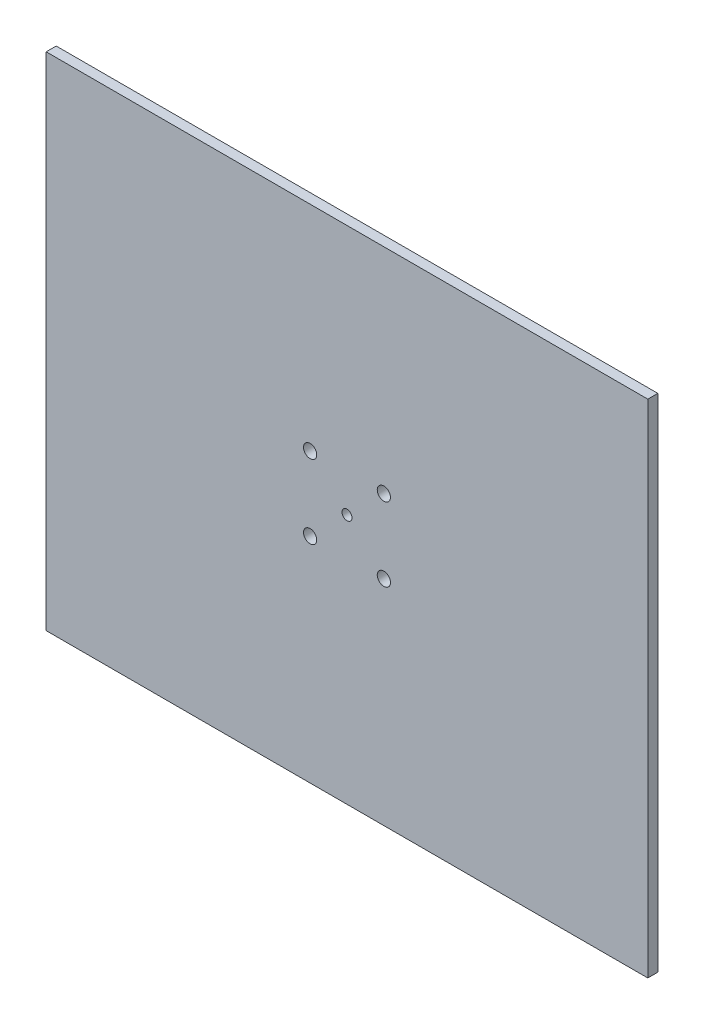
SolidWorks part; units mm, degrees
ref_plane "前视基准面" through (0, 0, 0) normal (0, 0, 1) x (1, 0, 0)
ref_plane "上视基准面" through (0, 0, 0) normal (0, 1, 0) x (1, 0, 0)
ref_plane "右视基准面" through (0, 0, 0) normal (1, 0, 0) x (0, 0, -1)
sketch "草图1" plane through (0, 0, 0) normal (0, 0, 1) x (1, 0, 0)
  line L0 (-18.3848, 18.3848) -> (0, 0) construction
  line L1 (150, -125) -> (-150, -125)
  line L2 (150, -125) -> (150, 125)
  line L3 (150, 125) -> (-150, 125)
  line L4 (-150, -125) -> (-150, 125)
  line L5 (150, -125) -> (-150, 125) construction
  line L6 (150, 125) -> (-150, -125) construction
  line L7 (0, 0) -> (0, 75.2853) construction
  line L8 (0, 0) -> (89.5261, 0) construction
  circle A0 centre (-18.3848, 18.3848) radius 3.3
  circle A1 centre (18.3848, 18.3848) radius 3.3
  circle A2 centre (18.3848, -18.3848) radius 3.3
  circle A3 centre (-18.3848, -18.3848) radius 3.3
  circle A4 centre (0, 0) radius 2.5
  point P0 (0, 0)
  dimension "D3" = 6.6
  dimension "D6" = 5
  dimension "D1" = 250
  dimension "D2" = 300
  dimension "D4" = 26
  dimension "D5" = 45
extrude "凸台-拉伸1" add sketch "草图1" along normal blind 5
